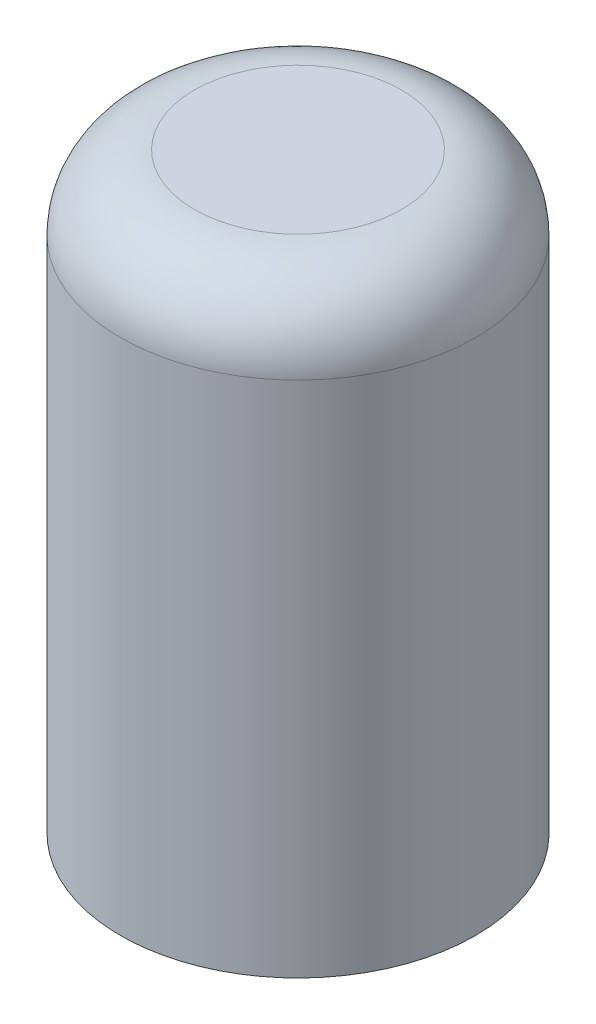
SolidWorks part; units mm, degrees
ref_plane "Front Plane" through (0, 0, 0) normal (0, 0, 1) x (1, 0, 0)
ref_plane "Top Plane" through (0, 0, 0) normal (0, 1, 0) x (1, 0, 0)
ref_plane "Right Plane" through (0, 0, 0) normal (1, 0, 0) x (0, 0, -1)
sketch "Sketch1" plane through (0, 0, 0) normal (0, 0, 1) x (1, 0, 0)
  line L0 (0, 0) -> (60, 0)
  line L1 (60, 0) -> (60, 175)
  line L2 (35, 200) -> (0, 200)
  line L3 (0, 200) -> (0, 0)
  arc A0 (60, 175) -> (35, 200) centre (35, 175) ccw
  dimension "D1" = 200
  dimension "D2" = 60
  dimension "D3" = 175
revolve "Revolve5" add sketch "Sketch1" angle 360 about L3
shell "Shell5" thickness 2
